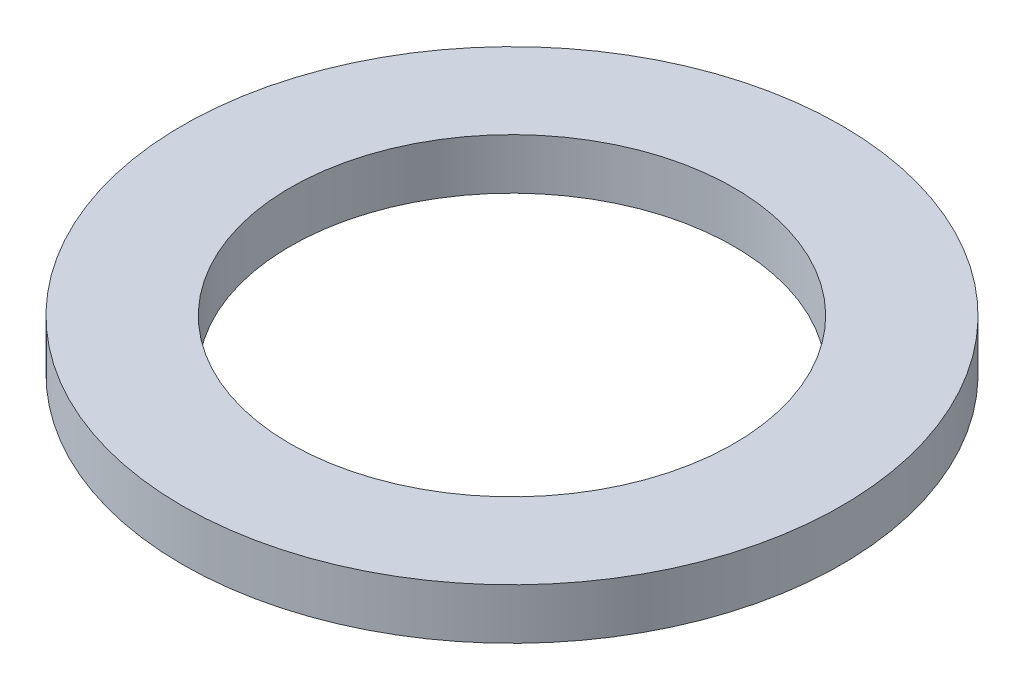
SolidWorks part; units mm, degrees
material "AISI 304"
ref_plane "前视基准面" through (0, 0, 0) normal (0, 0, 1) x (1, 0, 0)
ref_plane "上视基准面" through (0, 0, 0) normal (0, 1, 0) x (1, 0, 0)
ref_plane "右视基准面" through (0, 0, 0) normal (1, 0, 0) x (0, 0, -1)
other "Configuration Table"
sketch "草图1" plane through (0, 0, 0) normal (0, 1, 0) x (1, 0, 0)
  circle A0 centre (0, 0) radius 26
  circle A1 centre (0, 0) radius 17.5
  dimension "D1" = 35
  dimension "D2" = 52
extrude "凸台-拉伸1" add sketch "草图1" along normal blind 4
